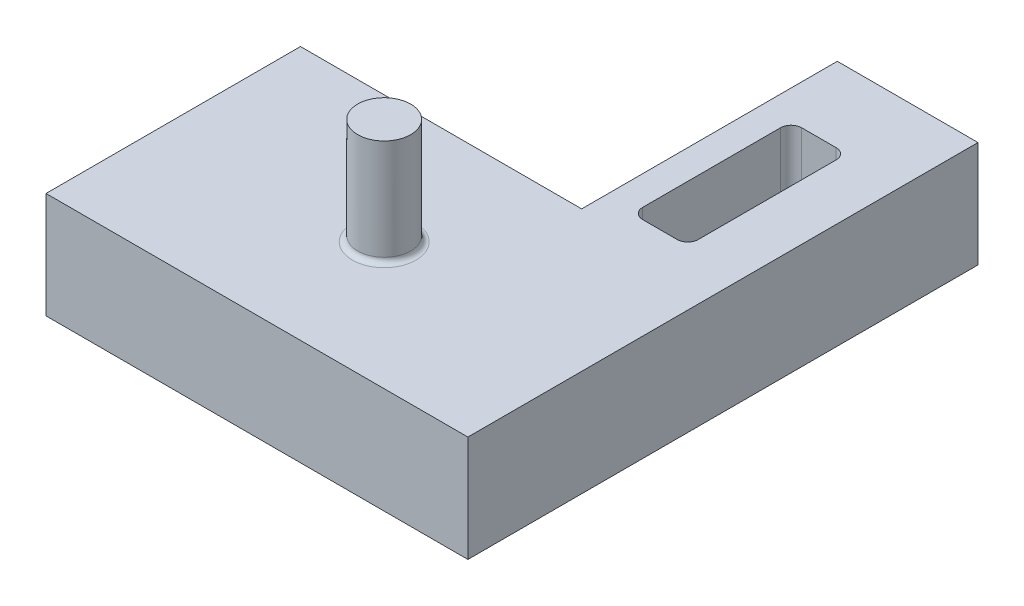
SolidWorks part; units mm, degrees
ref_plane "Front Plane" through (0, 0, 0) normal (0, 0, 1) x (1, 0, 0)
ref_plane "Top Plane" through (0, 0, 0) normal (0, 1, 0) x (1, 0, 0)
ref_plane "Right Plane" through (0, 0, 0) normal (1, 0, 0) x (0, 0, -1)
sketch "10" plane through (0, 0, 0) normal (0, 1, 0) x (1, 0, 0)
  line L0 (-15, 31.5) -> (15, 31.5) construction
  line L1 (-14.8938, 29.7182) -> (14.8938, 33.2818)
  line L2 (-14.8938, 29.7182) -> (-12, 15)
  line L3 (14.8938, 33.2818) -> (12, 48)
  line L4 (-12, 15) -> (0, 15)
  line L5 (12, 48) -> (0, 48)
  line L6 (0, 48) -> (0, 63)
  line L7 (0, 15) -> (0, 0)
  point P4 (0, 31.5)
  point P5 (0, 31.5)
  dimension "D1" = 15
  dimension "D2" = 12
  dimension "D3" = 15
  dimension "D4" = 30
  dimension "D5" = 30
  dimension "D6" = 15
  dimension "D7" = 0
  dimension "D8" = 0
  dimension "D9" = 31.5
sketch "01" plane through (0, 0, 0) normal (0, 1, 0) x (1, 0, 0)
  line L0 (-15, 31.5) -> (15, 31.5) construction
  line L1 (-9.3393, 19.7621) -> (9.3393, 43.2379)
  line L2 (-9.3393, 19.7621) -> (-12, 5)
  line L3 (9.3393, 43.2379) -> (12, 58)
  line L4 (-12, 5) -> (0, 5)
  line L5 (12, 58) -> (0, 58)
  line L6 (0, 58) -> (0, 73)
  line L7 (0, 5) -> (0, -10)
  point P4 (0, 31.5)
  point P5 (0, 31.5)
  dimension "D1" = 30
  dimension "D2" = 15
  dimension "D3" = 12
  dimension "D4" = 15
  dimension "D5" = 30
  dimension "D6" = 0
  dimension "D7" = 41.5
  dimension "D8" = 0
  dimension "D9" = 15
sketch "Sketch2" plane through (0, 0, 0) normal (0, 1, 0) x (1, 0, 0)
  line L1 (-19.8938, 77.5) -> (0, 77.5)
  line L2 (-19.8938, 77.5) -> (-19.8938, -14.5)
  line L3 (-19.8938, -14.5) -> (0, -14.5)
  line L9 (-15, 31.5) -> (15, 31.5) construction
  line L24 (0, 77.5) -> (0, 75.5)
  line L25 (-2.625, 73) -> (-2.625, 63)
  line L26 (0, 75.5) -> (-2.625, 75.5)
  line L27 (-2.625, 75.5) -> (-2.625, 73)
  line L28 (0, 60.5) -> (-2.625, 60.5)
  line L29 (-2.625, 60.5) -> (-2.625, 63)
  line L32 (0, 60.375) -> (0, 2.5)
  line L34 (0, 60.5) -> (0, 60.375)
  line L35 (-2.625, 0) -> (-2.625, -10)
  line L36 (0, 2.5) -> (-2.625, 2.5)
  line L37 (-2.625, 2.5) -> (-2.625, 0)
  line L38 (0, -12.5) -> (-2.625, -12.5)
  line L39 (-2.625, -12.5) -> (-2.625, -10)
  line L41 (0, -12.5) -> (0, -14.5)
  circle A7 centre (-14.8938, 29.7182) radius 5 construction
  circle A19 centre (0, 73) radius 2.625 construction
  circle A21 centre (0, 63) radius 2.625 construction
  circle A22 centre (0, 73) radius 2.5 construction
  circle A23 centre (0, 63) radius 2.5 construction
  circle A24 centre (0, -10) radius 2.625 construction
  circle A25 centre (0, 0) radius 2.625 construction
  circle A26 centre (0, 0) radius 2.5 construction
  circle A27 centre (0, -10) radius 2.5 construction
  dimension "D2" = 5.25
  dimension "D3" = 5.25
  dimension "D4" = 5
  dimension "D5" = 5
  dimension "D8" = 10
  dimension "D7" = 10
  dimension "D9" = 5.25
  dimension "D12" = 5.25
  dimension "D14" = 5
  dimension "D15" = 5
  dimension "D6" = 2
  dimension "D10" = 19.8938
  dimension "D11" = 5
  dimension "D13" = 19.8938
  dimension "D16" = 10
  dimension "D17" = 2
  dimension "D18" = 57.875
extrude "Boss-Extrude1" add sketch "Sketch2" along normal blind 10 contours L2 L3 L41 L38 L39 L35 L37 L36 L32 L34 L28 L29 L25 L27 L26 L24 L1
fillet "Fillet2" radius 1 4 edges at (-2.625, 5, 12.5) (-2.625, 5, -2.5) (-2.625, 5, -60.5) (-2.625, 5, -75.5)
mirror "Mirror1" of "Fillet2", "Boss-Extrude1"
sketch "Sketch4" plane through (0, 0, 0) normal (0, 1, 0) x (1, 0, 0)
  line L0 (-14.625, 15) -> (-14.625, 5)
  line L1 (-9.375, 15) -> (-9.375, 5)
  line L2 (-12, 2.5) -> (-9.375, 2.5)
  line L3 (-9.375, 2.5) -> (-9.375, 5)
  line L4 (-12, 2.5) -> (-14.625, 2.5)
  line L5 (-14.625, 2.5) -> (-14.625, 5)
  line L6 (-12, 17.5) -> (-9.375, 17.5)
  line L7 (-9.375, 17.5) -> (-9.375, 15)
  line L9 (-12, 17.5) -> (-14.625, 17.5)
  line L10 (-14.625, 17.5) -> (-14.625, 15)
  line L12 (9.375, 58) -> (9.375, 48)
  line L13 (14.625, 58) -> (14.625, 48)
  line L16 (12, 60.5) -> (9.375, 60.5)
  line L17 (9.375, 60.5) -> (9.375, 58)
  line L19 (12, 60.5) -> (14.625, 60.5)
  line L20 (14.625, 60.5) -> (14.625, 58)
  line L21 (12, 45.5) -> (14.625, 45.5)
  line L22 (14.625, 45.5) -> (14.625, 48)
  line L23 (12, 45.5) -> (9.375, 45.5)
  line L24 (9.375, 45.5) -> (9.375, 48)
  circle A0 centre (-12, 5) radius 2.625 construction
  circle A1 centre (-12, 15) radius 2.625 construction
  circle A14 centre (-12, 15) radius 2.5 construction
  circle A15 centre (-12, 5) radius 2.5 construction
  circle A16 centre (12, 48) radius 2.625 construction
  circle A17 centre (12, 48) radius 2.5 construction
  circle A18 centre (12, 58) radius 2.5 construction
  circle A19 centre (12, 58) radius 2.625 construction
  dimension "D1" = 5.25
  dimension "D2" = 5
extrude "Cut-Extrude1" cut sketch "Sketch4" along normal through all
fillet "Fillet3" radius 1 8 edges at (9.375, 5, -45.5) (14.625, 5, -45.5) (9.375, 5, -60.5) (14.625, 5, -60.5) (-14.625, 5, -2.5) (-9.375, 5, -2.5) (-9.375, 5, -17.5) (-14.625, 5, -17.5)
sketch "Sketch5" plane through (0, 10, 0) normal (0, 1, 0) x (1, 0, 0)
  line L0 (-14.8938, 29.7182) -> (14.8938, 33.2818) construction
  circle A0 centre (0, 31.5) radius 2.5
  dimension "D1" = 5
extrude "Boss-Extrude2" add sketch "Sketch5" along normal blind 10
fillet "Fillet1" radius 0.5 1 edges at (0, 10, -34)
sketch "Sketch6" plane through (0, 10, 0) normal (0, 1, 0) x (1, 0, 0)
  line L0 (19.8938, 77.5) -> (19.8938, 67.6092)
  line L9 (19.8938, 77.5) -> (19.8938, -14.5) construction
  line L12 (-6.625, 43.5) -> (55.225, 43.5) construction
  line L13 (6.625, 43.5) -> (-6.625, 43.5)
  line L15 (-19.8938, 77.5) -> (19.8938, 77.5) construction
  line L16 (-6.625, 124.9007) -> (-6.625, 43.5) construction
  line L17 (-6.625, 77.5) -> (19.8938, 77.5)
  line L18 (-6.625, 43.5) -> (-19.8938, 43.5)
  line L19 (-19.8938, 77.5) -> (-19.8938, -14.5) construction
  line L20 (-19.8938, 43.5) -> (-19.8938, 77.5)
  line L21 (-19.8938, 77.5) -> (-6.625, 77.5)
  line L22 (19.8938, 19.5) -> (-51.3, 19.5) construction
  line L23 (-19.8938, -14.5) -> (19.8938, -14.5)
  line L24 (-19.8938, -14.5) -> (-19.8938, 19.5)
  line L25 (-19.8938, 19.5) -> (19.8938, 19.5)
  line L26 (19.8938, -14.5) -> (19.8938, 19.5)
  line L27 (6.625, 99.3981) -> (6.625, 43.5) construction
  line L28 (6.625, 43.5) -> (6.625, 67.6092)
  line L29 (6.625, 67.6092) -> (19.8938, 67.6092)
extrude "Cut-Extrude2" cut sketch "Sketch6" against normal blind 10
